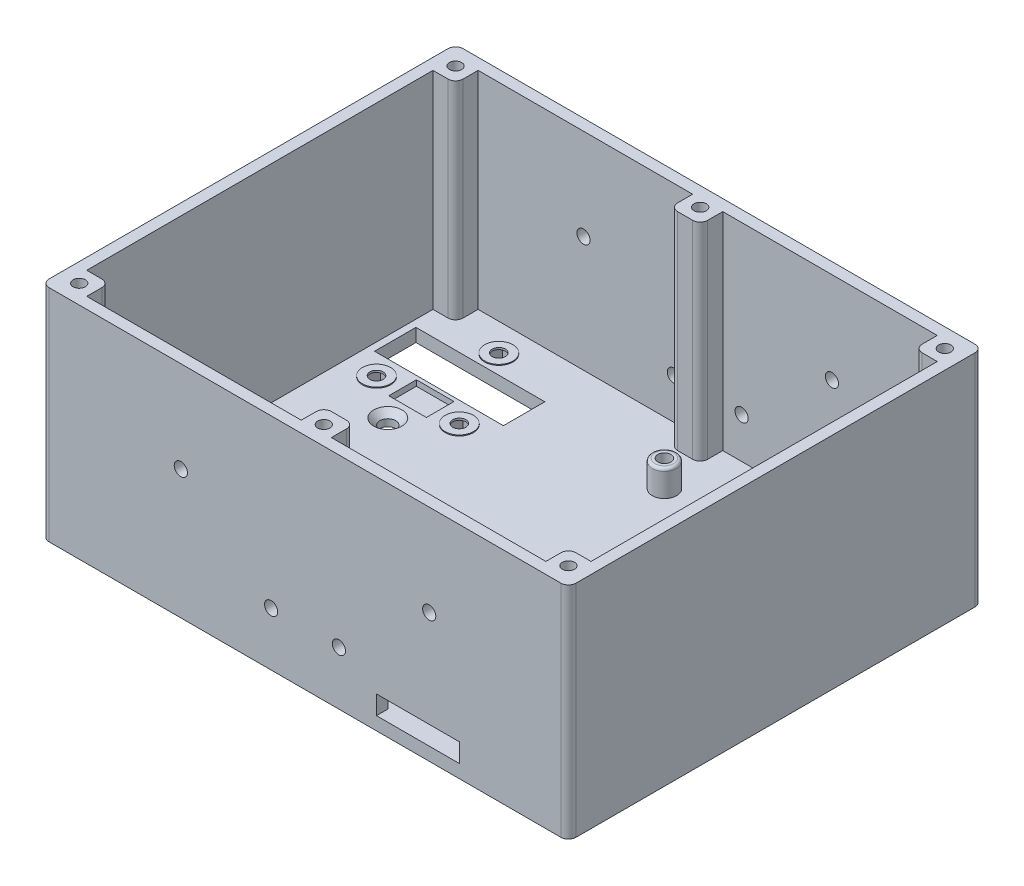
SolidWorks part; units mm, degrees
ref_plane "Front Plane" through (0, 0, 0) normal (0, 0, 1) x (1, 0, 0)
ref_plane "Top Plane" through (0, 0, 0) normal (0, 1, 0) x (1, 0, 0)
ref_plane "Right Plane" through (0, 0, 0) normal (1, 0, 0) x (0, 0, -1)
sketch "Sketch1" plane through (0, 0, 0) normal (0, 1, 0) x (1, 0, 0)
  line L1 (70, -55) -> (-70, -55)
  line L2 (70, -55) -> (70, 55)
  line L3 (70, 55) -> (-70, 55)
  line L4 (-70, -55) -> (-70, 55)
  line L5 (70, -55) -> (-70, 55) construction
  line L6 (70, 55) -> (-70, -55) construction
  point P0 (0, 0)
  dimension "D1" = 110
  dimension "D2" = 140
extrude "Bottom" add sketch "Sketch1" along normal blind 3.5
sketch "Sketch3" plane through (0, 3.5, 0) normal (0, 1, 0) x (1, 0, 0)
  line L0 (-70, 55) -> (70, 55)
  line L1 (70, 55) -> (70, -55)
  line L2 (70, -55) -> (-70, -55)
  line L3 (-70, -55) -> (-70, 55)
  line L4 (-61, 52) -> (-4, 52)
  line L5 (67, 46) -> (67, -46)
  line L6 (61, -52) -> (4, -52)
  line L7 (0, 55) -> (0, -55) construction
  line L8 (-67, 46) -> (-61, 46)
  line L9 (-61, 46) -> (-61, 52)
  line L10 (61, 52) -> (61, 46)
  line L11 (61, 46) -> (67, 46)
  line L12 (67, -46) -> (61, -46)
  line L13 (61, -46) -> (61, -52)
  line L14 (-67, -46) -> (-61, -46)
  line L15 (-61, -46) -> (-61, -52)
  line L16 (-67, -46) -> (-67, 46)
  line L17 (0, 0) -> (67, 0) construction
  line L18 (4, -52) -> (4, -46)
  line L19 (-4, 52) -> (-4, 46)
  line L20 (-4, 46) -> (4, 46)
  line L21 (4, 52) -> (4, 46)
  line L22 (0, 46) -> (0, 42.7097) construction
  line L23 (4, 52) -> (61, 52)
  line L24 (-4, -46) -> (4, -46)
  line L25 (-4, -52) -> (-4, -46)
  line L26 (-4, -52) -> (-61, -52)
  dimension "D1" = 3
  dimension "D2" = 3
  dimension "D3" = 3
  dimension "D4" = 3
  dimension "D5" = 6
  dimension "D6" = 8
extrude "Wall" add sketch "Sketch3" along normal blind 55
sketch "Sketch4" plane through (0, 58.5, 0) normal (0, 1, 0) x (1, 0, 0)
  line L0 (-70, 55) -> (-70, -55) construction
  line L1 (70, 55) -> (-70, 55) construction
  line L2 (70, -55) -> (70, 55) construction
  line L3 (-70, -55) -> (70, -55) construction
  line L4 (0, 55) -> (0, 30.3541) construction
  line L5 (70, 0) -> (33.8613, 0) construction
  circle A0 centre (-65, 50) radius 1.625
  circle A1 centre (65, 50) radius 1.625
  circle A2 centre (65, -50) radius 1.625
  circle A3 centre (-65, -50) radius 1.625
  circle A4 centre (0, 50) radius 1.625
  circle A5 centre (0, -50) radius 1.625
  dimension "D1" = 3.25
  dimension "D4" = 5
  dimension "D2" = 5
  dimension "D3" = 5
  dimension "D5" = 5
extrude "Top Plate Screw Holes" cut sketch "Sketch4" against normal blind 30 draft 1
fillet "Fillet14" radius 2 1 edges at (-4, 31, 46)
fillet "Fillet13" radius 2 1 edges at (4, 31, 46)
fillet "Fillet12" radius 2 1 edges at (-4, 31, -46)
fillet "Fillet11" radius 2 1 edges at (4, 31, -46)
fillet "Fillet1" radius 2 1 edges at (-61, 31, 46)
fillet "Fillet2" radius 2 1 edges at (61, 31, 46)
fillet "Fillet3" radius 2 1 edges at (61, 31, -46)
fillet "Fillet4" radius 2 1 edges at (-61, 31, -46)
fillet "Fillet5" radius 2 1 edges at (-70, 29.25, -55)
fillet "Fillet6" radius 2 1 edges at (70, 29.25, -55)
fillet "Fillet7" radius 2 1 edges at (70, 29.25, 55)
fillet "Fillet8" radius 2 1 edges at (-70, 29.25, 55)
sketch "M4 Mount" plane through (0, 3.5, 0) normal (0, -1, 0) x (1, 0, 0)
  line L0 (70, 53) -> (70, -53) construction
  line L1 (0, 0) -> (23.8675, 0) construction
  line L2 (0, 0) -> (0, -19.9393) construction
  circle A0 centre (48, -15) radius 2.1
  circle A1 centre (48, 20) radius 2.1
  circle A2 centre (-48, 20) radius 2.1
  circle A3 centre (-48, -15) radius 2.1
  dimension "D1" = 4.2
  dimension "D2" = 22
  dimension "D3" = 15
  dimension "D4" = 20
extrude "M4 Mount Cut" cut sketch "M4 Mount" along normal through all
sketch "M4 Screw Heads" plane through (0, 3.5, 0) normal (0, 1, 0) x (1, 0, 0)
  circle A0 centre (48, -20) radius 3.75
  circle A1 centre (48, 15) radius 3.75
  circle A2 centre (-48, 15) radius 3.75
  circle A3 centre (-48, -20) radius 3.75
  dimension "D1" = 7.5
extrude "Cut-Extrude3" cut sketch "M4 Screw Heads" against normal blind 10 draft 45
sketch "Sketch7" plane through (0, 0, 0) normal (0, -1, 0) x (1, 0, 0)
  line L2 (67, 46) -> (67, -46) construction
  line L5 (61, -52) -> (4, -52) construction
  circle A0 centre (41, -32) radius 7.5
  dimension "D1" = 15
  dimension "D2" = 26
  dimension "D3" = 20
extrude "USB Cabel Cut" cut sketch "Sketch7" against normal through all
fillet "Fillet9" radius 1 1 edges at (41, 0, -39.5)
fillet "Fillet10" radius 1 1 edges at (41, 3.5, -24.5)
sketch "Sketch14" plane through (0, 3.5, 0) normal (0, 1, 0) x (1, 0, 0)
  line L0 (67, -46) -> (67, 46) construction
  line L1 (59, 30) -> (51, 30)
  line L2 (59, 30) -> (59, 37)
  line L3 (59, 37) -> (51, 37)
  line L4 (51, 30) -> (51, 37)
  line L5 (59, 30) -> (51, 37) construction
  line L6 (59, 37) -> (51, 30) construction
  line L7 (61, 52) -> (4, 52) construction
  point P0 (0, 33.9149)
  dimension "D1" = 7
  dimension "D2" = 8
  dimension "D3" = 8
  dimension "D4" = 15
extrude "Boss-Extrude1" add sketch "Sketch14" along normal blind 6
sketch "Sketch16" plane through (18.1808, 0, -30) normal (0, 0, -1) x (-1, 0, 0)
  line L1 (-38.8192, 3.5) -> (-34.8192, 3.5)
  line L2 (-38.8192, 3.5) -> (-38.8192, 6.5)
  line L3 (-38.8192, 6.5) -> (-34.8192, 6.5)
  line L4 (-34.8192, 3.5) -> (-34.8192, 6.5)
  line L5 (-36.8192, 3.5) -> (-36.8192, 6.5) construction
  line L6 (-32.8192, 3.5) -> (-40.8192, 3.5) construction
  dimension "D1" = 4
  dimension "D3" = 3
extrude "Cut-Extrude6" cut sketch "Sketch16" along normal up to surface (7 mm away) up to face at (55, 6.5, -37)
sketch "Sketch9" plane through (0, 3.5, 0) normal (0, 1, 0) x (1, 0, 0)
  line L2 (5, 35.5) -> (-6, 35.5) construction
  line L3 (-6, 35.5) -> (-6, -39) construction
  line L6 (-6, -39) -> (13.1129, -39) construction
  line L7 (-2, -46) -> (2, -46) construction
  line L9 (0, 46) -> (0, 26) construction
  line L10 (2, 46) -> (-2, 46) construction
  circle A0 centre (-6, -39) radius 3.25
  circle A5 centre (5, 35.5) radius 3.25
  point P3 (0, -46)
  dimension "D1" = 6.5
  dimension "D4" = 7
  dimension "D2" = 11
  dimension "D3" = 74.5
  dimension "D5" = 5
extrude "Curcuit Board Mount Posts EXT" add sketch "Sketch9" along normal offset from surface (7 mm away) 1 up to face at (55, 9.5, -33.5) offset beyond the face yes
sketch "Sketch10" plane through (0, 10.5, 0) normal (0, 1, 0) x (1, 0, 0)
  circle A0 centre (5, 35.5) radius 1.75
  circle A1 centre (-6, -39) radius 1.75
  dimension "D1" = 3.5
extrude "M3 Screw Curcuit Mount CUT" cut sketch "Sketch10" against normal through all
sketch "Sketch11" plane through (0, 0, 0) normal (0, -1, 0) x (1, 0, 0)
  line L1 (-8.6639, 38.3172) -> (-6.7406, 36.3516)
  line L2 (-6.7406, 36.3516) -> (-4.0767, 37.0344)
  line L3 (-4.0767, 37.0344) -> (-3.3361, 39.6828)
  line L4 (-3.3361, 39.6828) -> (-5.2594, 41.6484)
  line L5 (-5.2594, 41.6484) -> (-7.9233, 40.9656)
  line L6 (-7.9233, 40.9656) -> (-8.6639, 38.3172)
  line L7 (5, -38.6754) -> (7.75, -37.0877)
  line L8 (7.75, -37.0877) -> (7.75, -33.9123)
  line L9 (7.75, -33.9123) -> (5, -32.3246)
  line L10 (5, -32.3246) -> (2.25, -33.9123)
  line L11 (2.25, -33.9123) -> (2.25, -37.0877)
  line L12 (2.25, -37.0877) -> (5, -38.6754)
  circle A0 centre (-6, 39) radius 2.3816 construction
  circle A1 centre (5, -35.5) radius 2.75 construction
  dimension "D1" = 5.5
  dimension "D2" = 5.5
extrude "M3 Head Circuit Mount CUT" cut sketch "Sketch11" against normal offset from surface (3.25 mm away) 0.25
fillet "Fillet15" radius 0.75 1 edges at (5, 10.5, -32.25)
fillet "Fillet16" radius 0.75 1 edges at (-6, 10.5, 42.25)
sketch "Sketch18" plane through (0, 0, -55) normal (0, 0, -1) x (-1, 0, 0)
  line L0 (-68, 29.25) -> (68, 29.25) construction
  line L1 (-68, 58.5) -> (-68, 0) construction
  line L2 (68, 0) -> (68, 58.5) construction
  line L3 (0, 58.5) -> (0, 29.25) construction
  line L4 (-68, 58.5) -> (68, 58.5) construction
  line L7 (-4, 58.5) -> (-4, 3.5) construction
  circle A0 centre (-33, 34.25) radius 1.75
  circle A1 centre (33, 34.25) radius 1.75
  circle A2 centre (-9, 14.25) radius 1.75
  circle A3 centre (9, 14.25) radius 1.75
  dimension "D1" = 3.5
  dimension "D2" = 33
  dimension "D3" = 33
  dimension "D4" = 5
  dimension "D5" = 15
  dimension "D6" = 5
extrude "TOP-Screw" cut sketch "Sketch18" against normal up to surface (3 mm away) up to face at (-32.5, 31, -52)
sketch "Sketch19" plane through (0, 0, -52) normal (0, 0, 1) x (1, 0, 0)
  line L0 (61, 3.5) -> (4, 3.5) construction
  line L1 (41, 3.5) -> (19, 3.5)
  line L2 (41, 3.5) -> (41, 8.5)
  line L3 (41, 8.5) -> (19, 8.5)
  line L4 (19, 3.5) -> (19, 8.5)
  line L5 (61, 58.5) -> (61, 3.5) construction
  line L6 (4, 58.5) -> (4, 3.5) construction
  dimension "D1" = 20
  dimension "D2" = 15
  dimension "D3" = 5
extrude "TOP-Cables" cut sketch "Sketch19" against normal blind 10
sketch "Sketch20" plane through (0, 0, 55) normal (0, 0, 1) x (1, 0, 0)
  line L1 (19, 3.5) -> (41, 3.5)
  line L2 (19, 3.5) -> (19, 8.5)
  line L3 (19, 8.5) -> (41, 8.5)
  line L4 (41, 3.5) -> (41, 8.5)
  line L5 (41, 8.5) -> (19, 8.5) construction
  line L7 (41, 3.5) -> (41, 8.5) construction
  line L9 (19, 8.5) -> (19, 3.5) construction
extrude "Bottom-Cables" cut sketch "Sketch20" against normal up to surface (3 mm away) up to face at (32.5, 31, 52)
sketch "Sketch21" plane through (0, 0, 55) normal (0, 0, 1) x (1, 0, 0)
  circle A0 centre (-33, 34.25) radius 1.75
  circle A1 centre (-9, 14.25) radius 1.75
  circle A2 centre (9, 14.25) radius 1.75
  circle A3 centre (33, 34.25) radius 1.75
  circle A5 centre (33, 34.25) radius 1.75 construction
  circle A6 centre (9, 14.25) radius 1.75 construction
  circle A7 centre (-9, 14.25) radius 1.75 construction
  circle A8 centre (-33, 34.25) radius 1.75 construction
extrude "Bottom-Screw" cut sketch "Sketch21" against normal up to surface (3 mm away) up to face at (-32.5, 31, 52)
sketch "Sketch22" plane through (0, 3.5, 0) normal (0, 1, 0) x (1, 0, 0)
  line L0 (-48, 44.5) -> (-48, 23) construction
  line L1 (-48, 23) -> (-59, 23) construction
  line L3 (-4, 52) -> (-61, 52) construction
  line L4 (-67, 46) -> (-67, -46) construction
  line L13 (-65.125, 28.6) -> (-30.875, 28.6)
  line L14 (-48, 28.6) -> (-48, 34.2847) construction
  line L15 (-65.125, 28.6) -> (-65.125, 39.6)
  line L16 (-65.125, 39.6) -> (-30.875, 39.6)
  line L17 (-30.875, 39.6) -> (-30.875, 28.6)
  dimension "D3" = 21.5
  dimension "D4" = 11
  dimension "D7" = 7.5
  dimension "D8" = 8
  dimension "D19" = 5.6
  dimension "D20" = 34.25
  dimension "D21" = 11
sketch "Sketch23" plane through (0, 3.5, 0) normal (0, 1, 0) x (1, 0, 0)
  line L0 (-48, 44.5) -> (-48, 23) construction
  line L1 (-59, 23) -> (-37, 23) construction
  circle A0 centre (-48, 44.5) radius 1.75
  circle A1 centre (-37, 23) radius 1.75
  circle A2 centre (-59, 23) radius 1.75
  dimension "D1" = 3.5
sketch "Sketch24" plane through (0, 3.5, 0) normal (0, 1, 0) x (1, 0, 0)
  circle A0 centre (-59, 23) radius 3.75
  circle A1 centre (-48, 44.5) radius 3.75
  circle A2 centre (-37, 23) radius 3.75
  circle A4 centre (-59, 23) radius 1.75 construction
  dimension "D1" = 2
extrude "Connectors Cut" cut sketch "Sketch22" against normal up to surface (3.5 mm away) up to face at (5, 0, -35.5)
extrude "Standoffs" add sketch "Sketch24" along normal blind 0.25
extrude "M3 Screw Hole" cut sketch "Sketch23" against normal through all both and the other way through all
sketch "Sketch25" plane through (0, 0, 0) normal (0, -1, 0) x (1, 0, 0)
  line L1 (-39.75, -23) -> (-38.375, -25.3816)
  line L2 (-38.375, -25.3816) -> (-35.625, -25.3816)
  line L3 (-35.625, -25.3816) -> (-34.25, -23)
  line L4 (-34.25, -23) -> (-35.625, -20.6184)
  line L5 (-35.625, -20.6184) -> (-38.375, -20.6184)
  line L6 (-38.375, -20.6184) -> (-39.75, -23)
  line L7 (-60.375, -25.3816) -> (-57.625, -25.3816)
  line L8 (-57.625, -25.3816) -> (-56.25, -23)
  line L9 (-56.25, -23) -> (-57.625, -20.6184)
  line L10 (-57.625, -20.6184) -> (-60.375, -20.6184)
  line L11 (-60.375, -20.6184) -> (-61.75, -23)
  line L12 (-61.75, -23) -> (-60.375, -25.3816)
  line L13 (-49.375, -46.8816) -> (-46.625, -46.8816)
  line L14 (-46.625, -46.8816) -> (-45.25, -44.5)
  line L15 (-45.25, -44.5) -> (-46.625, -42.1184)
  line L16 (-46.625, -42.1184) -> (-49.375, -42.1184)
  line L17 (-49.375, -42.1184) -> (-50.75, -44.5)
  line L18 (-50.75, -44.5) -> (-49.375, -46.8816)
  circle A0 centre (-37, -23) radius 2.3816 construction
  circle A1 centre (-59, -23) radius 2.3816 construction
  circle A2 centre (-48, -44.5) radius 2.3816 construction
  dimension "D1" = 5.5
  dimension "D2" = 5.5
  dimension "D3" = 5.5
extrude "M3 Nut" cut sketch "Sketch25" against normal offset from surface (3.25 mm away) 0.25 up to face at (-48, 3.5, -40.75)
sketch "Sketch26" plane through (0, 3.5, 0) normal (0, 1, 0) x (1, 0, 0)
  line L0 (-59, 23) -> (-39, 23) construction
  line L1 (-53, 27.6) -> (-43, 27.6)
  line L2 (-53, 27.6) -> (-53, 20.25)
  line L3 (-53, 20.25) -> (-43, 20.25)
  line L4 (-43, 27.6) -> (-43, 20.25)
  line L5 (-53, 23) -> (-43, 23) construction
  line L6 (-65.125, 28.6) -> (-30.875, 28.6) construction
  dimension "D5" = 6
  dimension "D1" = 2.75
  dimension "D2" = 10
  dimension "D3" = 20
  dimension "D4" = 1
extrude "Room for PCB pins" cut sketch "Sketch26" against normal blind 1.5
equation "\"BOXWALL\"=3"
equation "\"D2@Sketch3\"= \"BOXWALL\""
equation "\"D3@Sketch3\"=\"BOXWALL\""
equation "\"D4@Sketch3\"=\"BOXWALL\""
equation "\"SCREW_M3\"=3.5"
equation "\"D1@Sketch10\"=\"SCREW_M3\""
equation "\"SCREW_M3_HEAD\"=5.5"
equation "\"D1@Sketch11\"=\"SCREW_M3_HEAD\""
equation "\"D1@Sketch18\"=\"SCREW_M3\""
equation "\"D2@Sketch11\"=\"SCREW_M3_HEAD\""
equation "\"D1@Sketch23\"=\"SCREW_M3\""
equation "\"D1@Sketch25\"=\"SCREW_M3_HEAD\""
equation "\"D2@Sketch25\"=\"SCREW_M3_HEAD\""
equation "\"D3@Sketch25\"=\"SCREW_M3_HEAD\""
